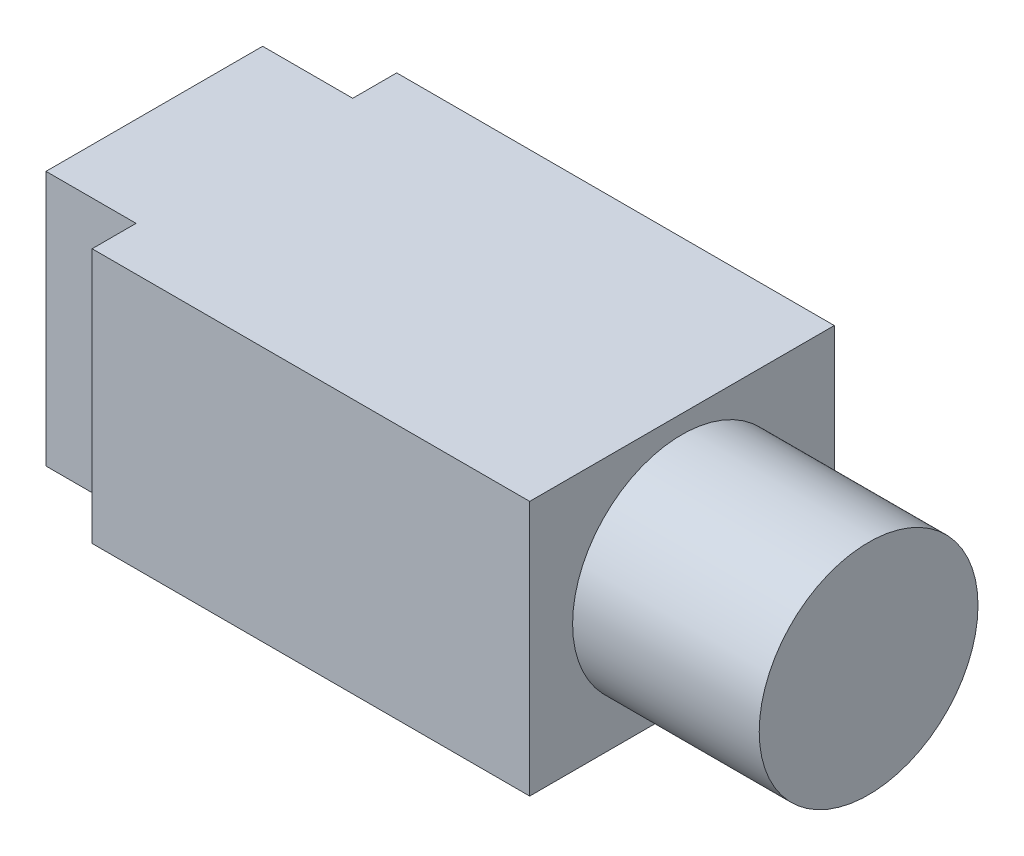
SolidWorks part; units mm, degrees
ref_plane "Front Plane" through (0, 0, 0) normal (0, 0, 1) x (1, 0, 0)
ref_plane "Top Plane" through (0, 0, 0) normal (0, 1, 0) x (1, 0, 0)
ref_plane "Right Plane" through (0, 0, 0) normal (1, 0, 0) x (0, 0, -1)
sketch "Sketch1" plane through (0, 0, 0) normal (0, 1, 0) x (1, 0, 0)
  line L0 (-10.2, -5.05) -> (-10.2, 5.05) construction
  line L1 (-10.2, -7.1) -> (10.2, -7.1)
  line L2 (-10.2, -7.1) -> (-10.2, 7.1)
  line L3 (-10.2, 7.1) -> (10.2, 7.1)
  line L4 (10.2, -7.1) -> (10.2, 7.1)
  line L5 (-10.2, -7.1) -> (10.2, 7.1) construction
  line L6 (-10.2, 7.1) -> (10.2, -7.1) construction
  line L8 (-10.2, 5.05) -> (-14.4, 5.05)
  line L9 (-10.2, 5.05) -> (-10.2, -5.05)
  line L10 (-10.2, -5.05) -> (-14.4, -5.05)
  line L11 (-14.4, 5.05) -> (-14.4, -5.05)
  point P0 (0, 0)
  point P9 (-10.2, 0)
  dimension "D1" = 20.4
  dimension "D2" = 14.2
  dimension "D3" = 10.1
  dimension "D4" = 4.2
extrude "Boss-Extrude1" add sketch "Sketch1" along normal mid plane 11.9 contours L8 L11 L10 L2 | L1 L4 L3 L2
sketch "Sketch2" plane through (10.2, 0, 0) normal (1, 0, 0) x (0, 0, -1)
  line L4 (-7.1, -5.95) -> (7.1, -5.95)
  line L5 (7.1, -5.95) -> (7.1, 5.95)
  line L6 (7.1, 5.95) -> (-7.1, 5.95)
  line L7 (-7.1, 5.95) -> (-7.1, -5.95)
  line L8 (-7.1, -5.95) -> (7.1, -5.95)
  line L9 (7.1, -5.95) -> (7.1, 5.95)
  line L11 (-7.1, 5.95) -> (-7.1, -5.95)
  circle A1 centre (0, 0) radius 5.1
  dimension "D2" = 10.2
  dimension "D1" = 0
extrude "Boss-Extrude2" add sketch "Sketch2" along normal blind 8.7 contours A1
